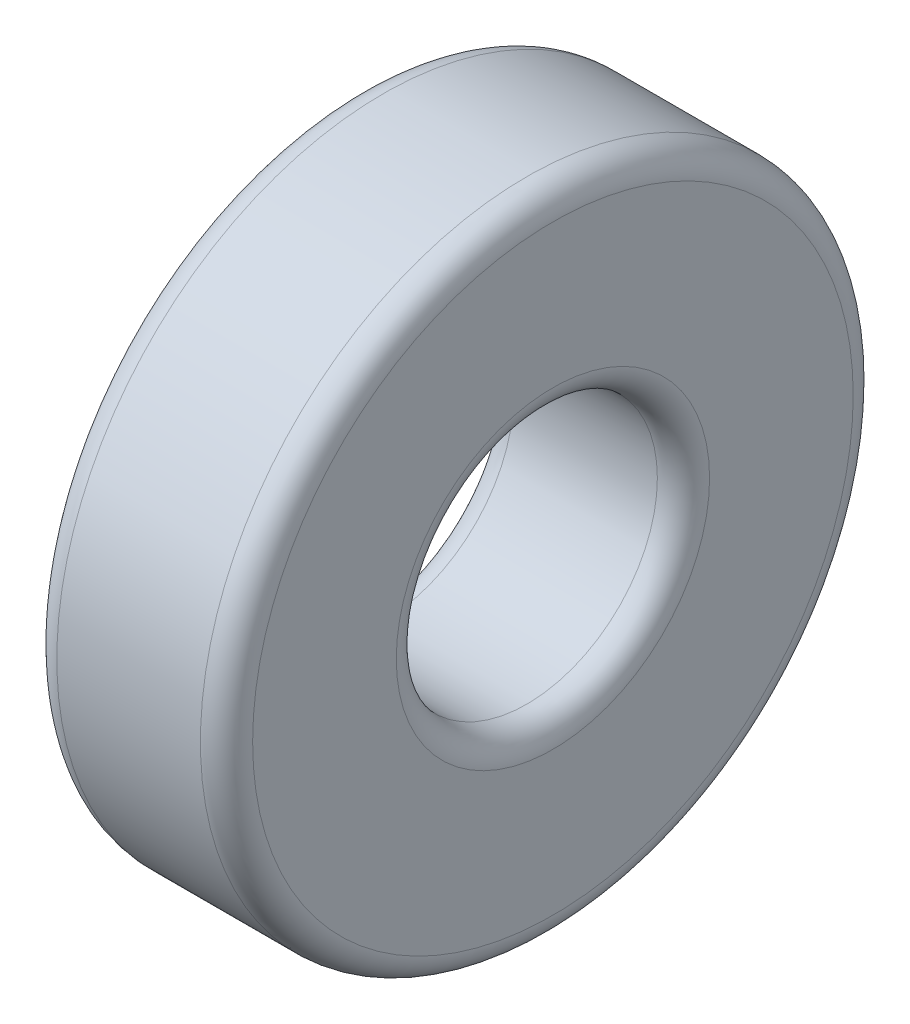
SolidWorks part; units mm, degrees
material "ABS"
ref_plane "Front Plane" through (0, 0, 0) normal (1, 0, 0) x (0, 1, 0)
ref_plane "Top Plane" through (0, 0, 0) normal (0, 0, 1) x (0, 1, 0)
ref_plane "Right Plane" through (0, 0, 0) normal (0, 1, 0) x (-1, 0, 0)
sketch "Sketch1" plane through (0, 0, 0) normal (0, 1, 0) x (-1, 0, 0)
  line L0 (2.75, 12.5) -> (-2.75, 12.5)
  line L1 (-3.75, 11.5) -> (-3.75, 6)
  line L2 (-2.75, 5) -> (2.75, 5)
  line L3 (3.75, 11.5) -> (3.75, 6)
  line L4 (3.1111, 0) -> (27.3333, 0) construction
  arc A0 (2.75, 5) -> (3.75, 6) centre (2.75, 6) ccw
  arc A1 (-3.75, 6) -> (-2.75, 5) centre (-2.75, 6) ccw
  arc A2 (-2.75, 12.5) -> (-3.75, 11.5) centre (-2.75, 11.5) ccw
  arc A3 (2.75, 12.5) -> (3.75, 11.5) centre (2.75, 11.5) cw
  point P3 (0, 5)
  point P15 (-3.75, 12.5)
  point P18 (3.75, 12.5)
  dimension "D4" = 1
  dimension "D1" = 10
  dimension "D2" = 25
  dimension "D3" = 7.5
revolve "Revolve1" add sketch "Sketch1" angle 360 about L4
